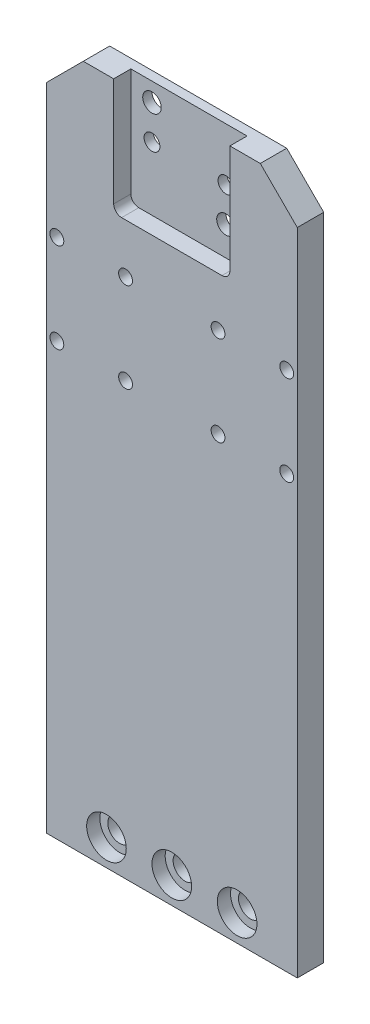
SolidWorks part; units mm, degrees
ref_plane "Piano frontale" through (0, 0, 0) normal (0, 0, 1) x (1, 0, 0)
ref_plane "Piano superiore" through (0, 0, 0) normal (0, 1, 0) x (1, 0, 0)
ref_plane "Piano destro" through (0, 0, 0) normal (1, 0, 0) x (0, 0, -1)
sketch "Schizzo1" plane through (0, 0, 0) normal (0, 0, 1) x (1, 0, 0)
  line L0 (105.684, 10) -> (-14.7585, 10) construction
  line L1 (0, 0) -> (95, 0)
  line L2 (0, 0) -> (0, 246)
  line L3 (14, 260) -> (81, 260)
  line L4 (95, 0) -> (95, 246)
  line L5 (47.5, 210) -> (47.5, 0) construction
  line L6 (131.5763, 163.3) -> (-32.5048, 163.3) construction
  line L7 (131.5763, 197.3) -> (-32.5048, 197.3) construction
  line L8 (0, 180.3) -> (95, 180.3) construction
  line L9 (0, 246) -> (14, 260)
  line L10 (81, 260) -> (95, 246)
  circle A0 centre (22.7707, 10) radius 4.2
  circle A1 centre (47.5, 10) radius 4.2
  circle A2 centre (72.2293, 10) radius 4.2
  circle A3 centre (4, 163.3) radius 2.6183
  circle A4 centre (30, 163.3) radius 2.6183
  circle A5 centre (65, 163.3) radius 2.6183
  circle A6 centre (91, 163.3) radius 2.6183
  circle A7 centre (91, 197.3) radius 2.6183
  circle A8 centre (65, 197.3) radius 2.6183
  circle A9 centre (30, 197.3) radius 2.6183
  circle A10 centre (4, 197.3) radius 2.6183
  point P1 (95, 260)
  point P2 (0, 260)
  dimension "D4" = 8.4
  dimension "D1" = 260
  dimension "D2" = 95
  dimension "D3" = 10
  dimension "D5" = 96.7
  dimension "D6" = 62.7
  dimension "D7" = 4
  dimension "D8" = 30
  dimension "D9" = 17
extrude "Estrusione-Estrusione1" add sketch "Schizzo1" against normal blind 10
sketch "Schizzo2" plane through (0, 0, 0) normal (0, 0, 1) x (1, 0, 0)
  line L0 (47.5, 260) -> (47.5, 0) construction
  line L1 (81, 260) -> (14, 260) construction
  line L2 (0, 0) -> (95, 0) construction
  line L3 (25.5044, 260) -> (25.5044, 219)
  line L4 (28.5044, 216) -> (66.4956, 216)
  line L5 (69.4956, 260) -> (69.4956, 219)
  line L6 (25.5044, 260) -> (69.4956, 260)
  arc A0 (28.5044, 216) -> (25.5044, 219) centre (28.5044, 219) cw
  arc A1 (66.4956, 216) -> (69.4956, 219) centre (66.4956, 219) ccw
  point P11 (25.5044, 216)
  point P13 (47.5, 216)
  dimension "D2" = 3
  dimension "D1" = 44
extrude "Taglio-Estrusione1" cut sketch "Schizzo2" against normal blind 6.5
sketch "Schizzo3" plane through (0, 0, -6.5) normal (0, 0, 1) x (1, 0, 0)
  line L0 (69.4956, 260) -> (25.5044, 260) construction
  line L1 (0, 246) -> (0, 0) construction
  circle A0 centre (33.5, 253) radius 3.5
  circle A1 centre (33.5, 240) radius 3
  circle A2 centre (61.5, 240) radius 3
  circle A3 centre (61.5, 227) radius 3.5
  dimension "D1" = 7
  dimension "D2" = 6
  dimension "D3" = 6
  dimension "D4" = 7
  dimension "D5" = 7
  dimension "D6" = 20
  dimension "D7" = 20
  dimension "D8" = 33
  dimension "D9" = 33.5
  dimension "D10" = 33.5
  dimension "D11" = 61.5
  dimension "D12" = 61.5
extrude "Taglio-Estrusione2" cut sketch "Schizzo3" against normal blind 6.5
hole_wizard "Foro lamato per Vite M8 a testa cilindrica piana-1" positions "Schizzo3D1" profile "Schizzo4" counterbore size "M8" standard "ISO"
sketch3d "Schizzo3D1"
  line L0 (47.5, 10, -10) -> (47.5, 10, 0) construction
  line L2 (22.7707, 10, -10) -> (22.7707, 10, 0) construction
  line L3 (72.2293, 10, -10) -> (72.2293, 10, 0) construction
  circle A0 centre (22.7707, 10, 0) radius 4.2 construction
  circle A1 centre (72.2293, 10, 0) radius 4.2 construction
  point P0 (26.3771, 7.8474, 0)
  point P4 (22.7707, 10, 4.2)
  point P5 (47.5, 10, 0)
  point P7 (72.7247, 5.8293, 0)
  point P11 (72.2293, 10, 4.2)
  point P19 (22.9699, 5.8047, 0)
  point P21 (71.288, 5.9068, 0)
  point P27 (22.7707, 10, 0)
  point P34 (72.2293, 10, 0)
sketch "Schizzo4" plane through (47.5, 10, 0) normal (1, 0, 0) x (0, -1, 0)
  line L0 (0, 0) -> (0, 10)
  line L1 (0, 10) -> (4.5, 10)
  line L3 (4.5, 10) -> (4.5, 5)
  line L4 (4.5, 5) -> (7.5, 5)
  line L5 (7.5, 5) -> (7.5, 0)
  line L7 (7.5, 0) -> (0, 0)
  line L11 (0, -6.35) -> (0, 107.95) construction
  dimension "Thru Hole Dia." = 9
  dimension "Thru Hole Depth" = 10
  dimension "C'Bore Dia." = 15
  dimension "C'Bore Depth" = 5
